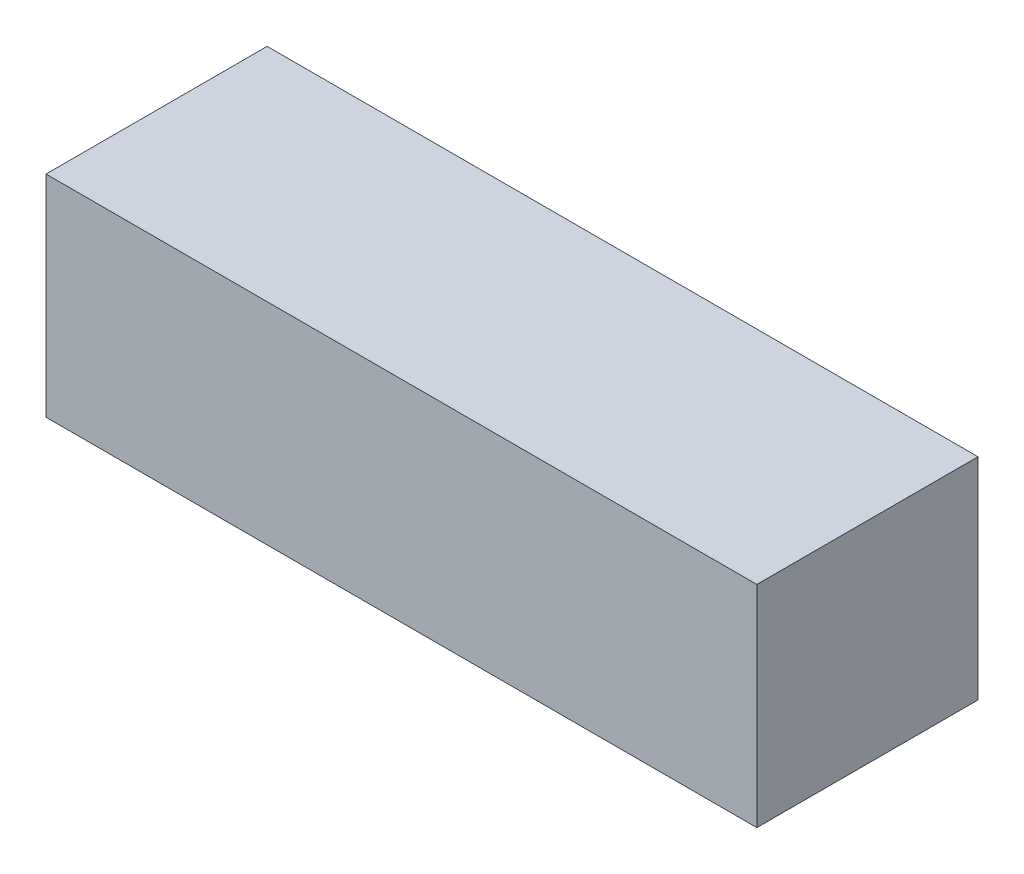
SolidWorks part; units mm, degrees
ref_plane "Front Plane" through (0, 0, 0) normal (0, 0, 1) x (1, 0, 0)
ref_plane "Top Plane" through (0, 0, 0) normal (0, 1, 0) x (1, 0, 0)
ref_plane "Right Plane" through (0, 0, 0) normal (1, 0, 0) x (0, 0, -1)
sketch "Sketch1" plane through (0, 0, 0) normal (0, 1, 0) x (1, 0, 0)
  line L1 (67.5, -21) -> (-67.5, -21)
  line L2 (67.5, -21) -> (67.5, 21)
  line L3 (67.5, 21) -> (-67.5, 21)
  line L4 (-67.5, -21) -> (-67.5, 21)
  line L5 (67.5, -21) -> (-67.5, 21) construction
  line L6 (67.5, 21) -> (-67.5, -21) construction
  point P0 (0, 0)
  dimension "D1" = 135
  dimension "D2" = 42
extrude "Boss-Extrude1" add sketch "Sketch1" along normal blind 40
